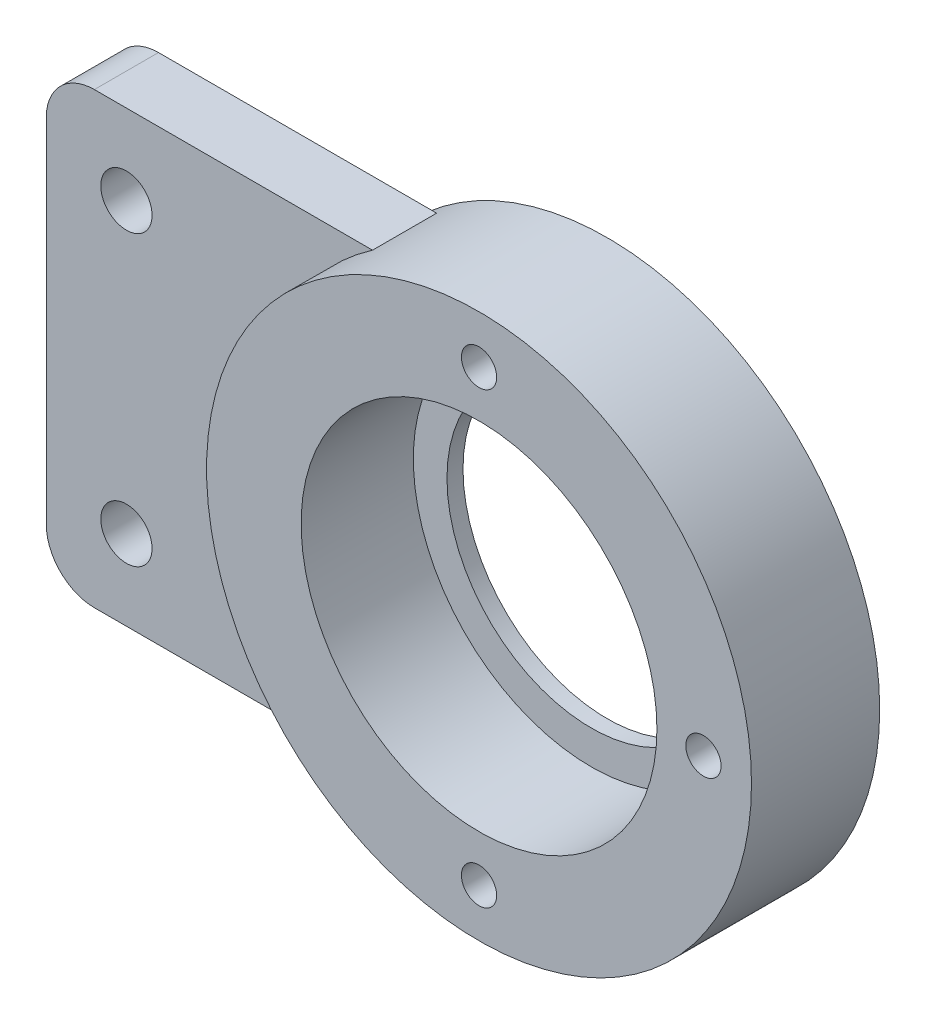
SolidWorks part; units mm, degrees
ref_plane "Front Plane" through (0, 0, 0) normal (0, 0, 1) x (1, 0, 0)
ref_plane "Top Plane" through (0, 0, 0) normal (0, 1, 0) x (1, 0, 0)
ref_plane "Right Plane" through (0, 0, 0) normal (1, 0, 0) x (0, 0, -1)
sketch "Bearing_housing_profile" plane through (0, 0, 0) normal (0, 0, 1) x (1, 0, 0)
  circle A0 centre (0, 0) radius 17
  circle A1 centre (0, 0) radius 11.1
  dimension "D1" = 34
  dimension "D2" = 22.2
extrude "Bearing_housing" add sketch "Bearing_housing_profile" along normal blind 7
sketch "Mounting_web_profile" plane through (0, 0, 0) normal (0, 0, 1) x (1, 0, 0)
  line L1 (-30, -14) -> (0, -14)
  line L2 (-30, -14) -> (-30, 14)
  line L3 (-30, 14) -> (0, 14)
  line L4 (0, -14) -> (0, 14)
  dimension "D1" = 30
  dimension "D2" = 28
  dimension "D3" = 14
extrude "Mounting_web" add sketch "Mounting_web_profile" along normal blind 4
sketch "Bearing_seat_profile" plane through (0, 0, 0) normal (0, 0, 1) x (1, 0, 0)
  circle A0 centre (0, 0) radius 11.1
  dimension "D1" = 22.2
extrude "Bearing_seat" cut sketch "Bearing_seat_profile" along normal through all from offset 50
sketch "Inner_outer_race_retaining_lip_profile" plane through (0, 0, 0) normal (0, 0, 1) x (1, 0, 0)
  circle A0 centre (0, 0) radius 17
  circle A1 centre (0, 0) radius 9
  dimension "D1" = 34
  dimension "D2" = 18
extrude "Inner_outer_race_retaining_lip" add sketch "Inner_outer_race_retaining_lip_profile" along normal blind 1 from offset 1
sketch "Standoff_fasteners_profile" plane through (0, 0, 0) normal (0, 0, 1) x (1, 0, 0)
  circle A0 centre (-25, -9) radius 1.6
  circle A1 centre (-25, 9) radius 1.6
  dimension "D1" = 3.2
  dimension "D2" = 3.2
  dimension "D3" = 25
  dimension "D4" = 9
  dimension "D5" = 9
extrude "Standoff_fasteners" cut sketch "Standoff_fasteners_profile" along normal through all from offset 50
sketch "Bearing_keeper_fasteners_profile" plane through (0, 0, 0) normal (0, 0, 1) x (1, 0, 0)
  circle A0 centre (14, 0) radius 1.1
  circle A1 centre (0, -14) radius 1.1
  circle A2 centre (0, 14) radius 1.1
  dimension "D1" = 2.2
  dimension "D2" = 2.2
  dimension "D3" = 2.2
  dimension "D4" = 14
  dimension "D5" = 14
  dimension "D6" = 14
extrude "Bearing_keeper_fasteners" cut sketch "Bearing_keeper_fasteners_profile" along normal through all from offset 50
fillet "Fillet1" radius 3 2 edges at (-30, -14, 2) (-30, 14, 2)
